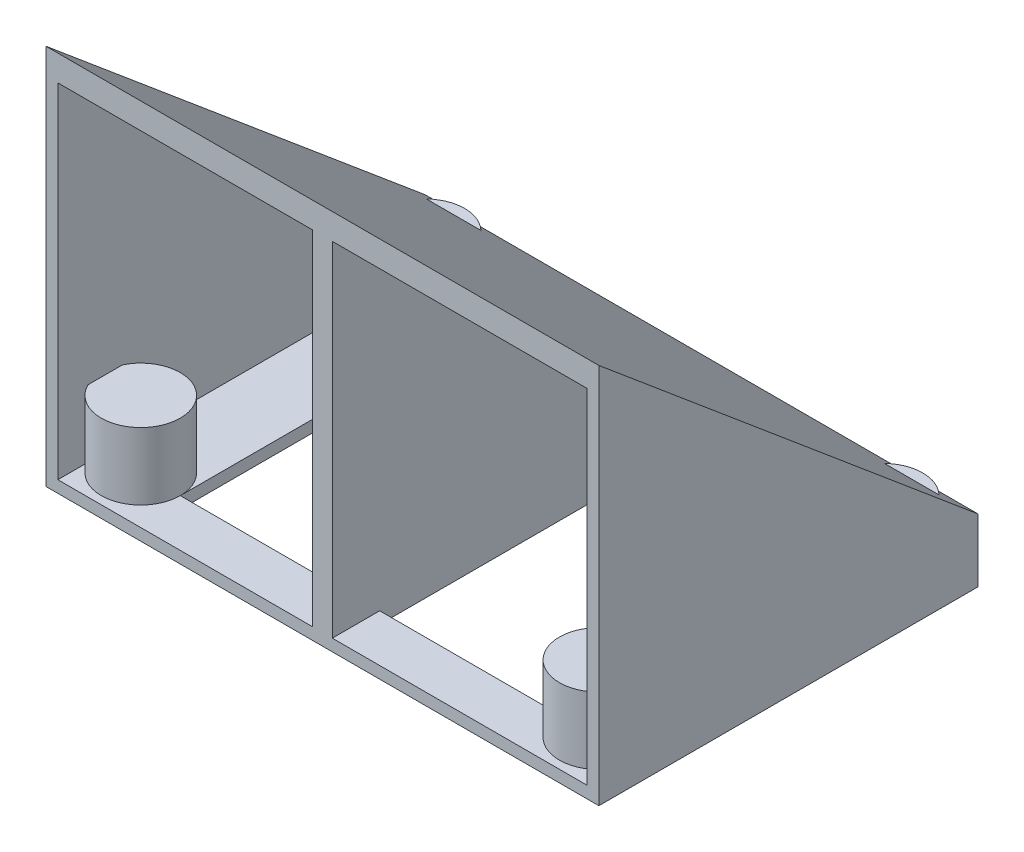
SolidWorks part; units mm, degrees
ref_plane "Front Plane" through (0, 0, 0) normal (0, 0, 1) x (1, 0, 0)
ref_plane "Top Plane" through (0, 0, 0) normal (0, 1, 0) x (1, 0, 0)
ref_plane "Right Plane" through (0, 0, 0) normal (1, 0, 0) x (0, 0, -1)
sketch "Sketch1" plane through (0, 0, 0) normal (0, 1, 0) x (1, 0, 0)
  line L1 (-46.9916, 21.479) -> (23.0084, 21.479)
  line L2 (-46.9916, 21.479) -> (-46.9916, -26.521)
  line L3 (-46.9916, -26.521) -> (23.0084, -26.521)
  line L4 (23.0084, 21.479) -> (23.0084, -26.521)
  dimension "D1" = 48
  dimension "D2" = 70
extrude "Boss-Extrude1" add sketch "Sketch1" along normal blind 1.5
sketch "Sketch6" plane through (23.0084, 0, 0) normal (1, 0, 0) x (0, 0, -1)
  line L0 (21.479, 0) -> (21.479, 8)
  line L1 (21.479, 8) -> (-26.521, 48.2768)
  line L2 (-26.521, 45.0133) -> (-26.521, 0)
  line L3 (-26.521, 0) -> (21.479, 0) construction
  line L4 (18.979, 0) -> (18.979, 6.8342)
  line L5 (18.979, 6.8342) -> (-24.021, 42.9155)
  line L6 (-24.021, 42.9155) -> (-26.521, 45.0133)
  line L7 (-24.021, 42.9155) -> (-24.021, 0) construction
  line L8 (-26.521, 48.2768) -> (-26.521, 0) construction
  line L9 (-26.521, 48.2768) -> (-26.521, 45.0133)
  line M7 (21.479, 1.5) -> (-26.521, 1.5)
  dimension "D1" = 8
  dimension "D2" = 40
  dimension "D3" = 2.5
extrude "Boss-Extrude6" add sketch "Sketch6" against normal blind 70 contours L1 L9 L6 L5 L4 L0 M7
sketch "Sketch7" plane through (23.0084, 0, 0) normal (1, 0, 0) x (0, 0, -1)
  line L0 (-26.521, 1.5) -> (18.979, 1.5) construction
  line L1 (18.979, 1.5) -> (18.979, 6.8342) construction
  line L2 (18.979, 6.8342) -> (-26.521, 45.0133) construction
  line L3 (-26.521, 1.5) -> (18.979, 1.5)
  line L4 (18.979, 1.5) -> (18.979, 6.8342)
  line L5 (18.979, 6.8342) -> (-26.521, 45.0133)
  line L6 (-26.521, 45.0133) -> (-26.521, 1.5)
extrude "Boss-Extrude7" add sketch "Sketch7" against normal blind 1.5
sketch "Sketch8" plane through (-46.9916, 0, 0) normal (-1, 0, 0) x (0, 0, 1)
  line L0 (-18.979, 6.8342) -> (26.521, 45.0133) construction
  line L1 (-18.979, 1.5) -> (-18.979, 6.8342) construction
  line L2 (-18.979, 1.5) -> (26.521, 1.5) construction
  line L3 (-18.979, 6.8342) -> (26.521, 45.0133)
  line L4 (-18.979, 1.5) -> (-18.979, 6.8342)
  line L5 (-18.979, 1.5) -> (26.521, 1.5)
  line L6 (26.521, 1.5) -> (26.521, 45.0133)
extrude "Boss-Extrude8" add sketch "Sketch8" against normal blind 1.5
sketch "Sketch9" plane through (0, 0, 0) normal (0, -1, 0) x (1, 0, 0)
  line L0 (17.0084, -21.479) -> (17.0084, 26.521) construction
  line L1 (23.0084, -21.479) -> (-46.9916, -21.479) construction
  line L2 (-46.9916, 26.521) -> (23.0084, 26.521) construction
  line L3 (-40.9916, -21.479) -> (-40.9916, 26.521) construction
  line L4 (-46.9916, -15.479) -> (23.0084, -15.479) construction
  line L5 (-46.9916, -21.479) -> (-46.9916, 26.521) construction
  line L6 (23.0084, 26.521) -> (23.0084, -21.479) construction
  line L7 (23.0084, 20.521) -> (-46.9916, 20.521) construction
  circle A0 centre (17.0084, -15.479) radius 5
  circle A1 centre (-40.9916, -15.479) radius 5
  circle A2 centre (-40.9916, 20.521) radius 5
  circle A3 centre (17.0084, 20.521) radius 5
  dimension "D5" = 10
  dimension "D6" = 10
  dimension "D7" = 10
  dimension "D8" = 10
  dimension "D1" = 6
  dimension "D2" = 6
  dimension "D3" = 6
  dimension "D4" = 6
extrude "Boss-Extrude9" add sketch "Sketch9" against normal blind 10
sketch "Sketch10" plane through (0, 0, 0) normal (0, -1, 0) x (1, 0, 0)
  circle A0 centre (17.0084, -15.479) radius 2.8
  circle A1 centre (-40.9916, -15.479) radius 2.8
  circle A2 centre (-40.9916, 20.521) radius 2.8
  circle A3 centre (17.0084, 20.521) radius 2.8
  dimension "D1" = 5.6
  dimension "D2" = 5.6
  dimension "D3" = 5.6
  dimension "D4" = 5.6
extrude "Cut-Extrude1" cut sketch "Sketch10" against normal blind 8
sketch "Sketch11" plane through (0, 0, 0) normal (0, -1, 0) x (1, 0, 0)
  line L1 (12.0084, -15.479) -> (-35.9916, -15.479)
  line L2 (12.0084, -15.479) -> (12.0084, 20.521)
  line L3 (12.0084, 20.521) -> (-35.9916, 20.521)
  line L4 (-35.9916, -15.479) -> (-35.9916, 20.521)
  circle A0 centre (17.0084, -15.479) radius 5 construction
  circle A1 centre (-40.9916, 20.521) radius 5 construction
  circle A2 centre (17.0084, -15.479) radius 5
  circle A3 centre (-40.9916, 20.521) radius 5
extrude "Cut-Extrude2" cut sketch "Sketch11" against normal blind 1.6 contours L4 L1 L2 L3
sketch "Sketch12" plane through (0, 0, 0) normal (0, -1, 0) x (1, 0, 0)
  line L0 (23.0084, -21.479) -> (-46.9916, -21.479) construction
  line L1 (-13.2416, -21.479) -> (-10.7416, -21.479)
  line L2 (-13.2416, -21.479) -> (-13.2416, 26.521)
  line L3 (-13.2416, 26.521) -> (-10.7416, 26.521)
  line L4 (-10.7416, -21.479) -> (-10.7416, 26.521)
  line L5 (-46.9916, 26.521) -> (23.0084, 26.521) construction
  line L6 (-11.9916, -21.479) -> (-11.9916, 26.521) construction
  line L7 (23.0084, 26.521) -> (23.0084, -21.479) construction
  dimension "D1" = 35
  dimension "D2" = 2.5
extrude "Boss-Extrude10" add sketch "Sketch12" against normal up to next
